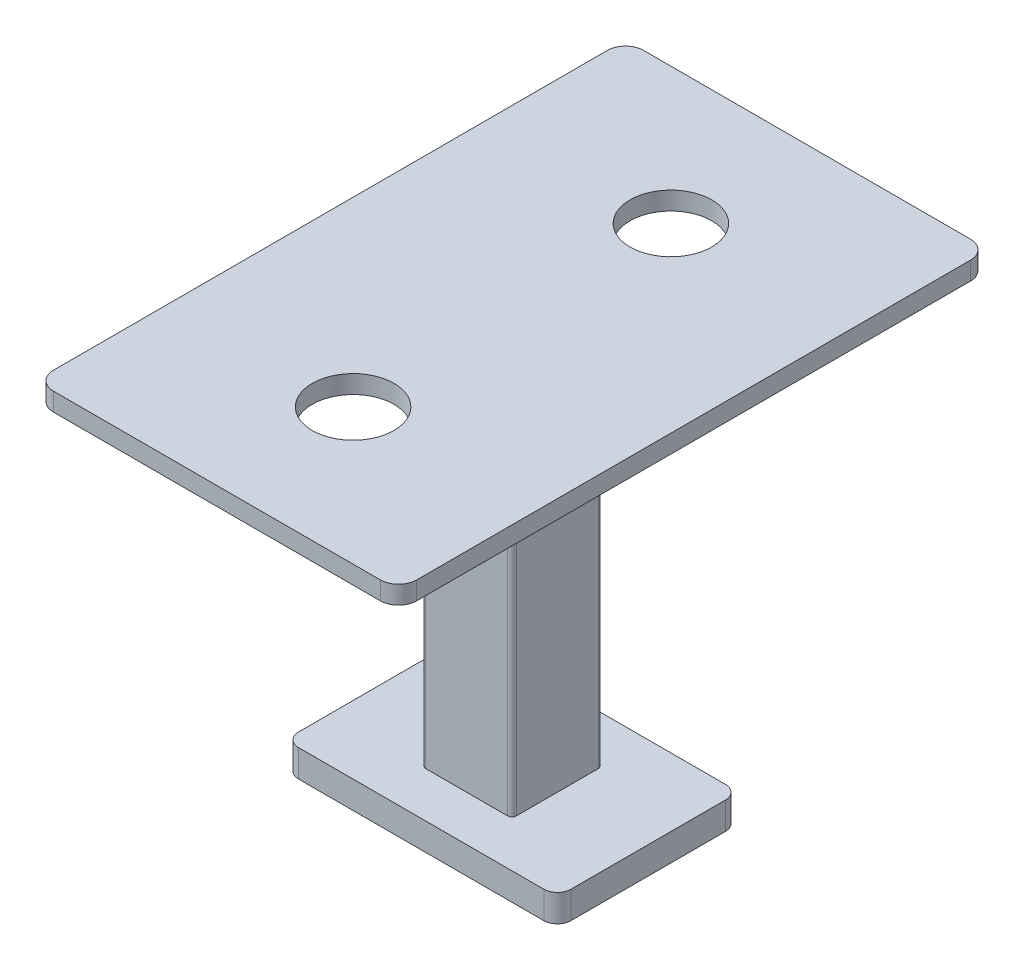
SolidWorks part; units mm, degrees
ref_plane "Front Plane" through (0, 0, 0) normal (0, 0, 1) x (1, 0, 0)
ref_plane "Top Plane" through (0, 0, 0) normal (0, 1, 0) x (1, 0, 0)
ref_plane "Right Plane" through (0, 0, 0) normal (1, 0, 0) x (0, 0, -1)
sketch "Sketch1" plane through (0, 0, 0) normal (0, 1, 0) x (1, 0, 0)
  line L0 (1.5, 0) -> (28.5, 0)
  line L1 (30, 1.5) -> (30, 18.5)
  line L2 (28.5, 20) -> (1.5, 20)
  line L3 (0, 18.5) -> (0, 1.5)
  arc A0 (30, 18.5) -> (28.5, 20) centre (28.5, 18.5) ccw
  arc A1 (30, 1.5) -> (28.5, 0) centre (28.5, 1.5) cw
  arc A2 (1.5, 0) -> (0, 1.5) centre (1.5, 1.5) cw
  arc A3 (1.5, 20) -> (0, 18.5) centre (1.5, 18.5) ccw
  point P7 (30, 20)
  point P10 (30, 0)
  point P13 (0, 0)
  dimension "D3" = 1.5
  dimension "D1" = 30
  dimension "D2" = 20
extrude "Boss-Extrude1" add sketch "Sketch1" along normal blind 3 contours L2 A3 L3 A2 L0 A1 L1 A0
sketch "Sketch3" plane through (0, 3, 0) normal (0, 1, 0) x (1, 0, 0)
  line L0 (15, 20) -> (15, 0) construction
  line L1 (28.5, 20) -> (1.5, 20) construction
  line L2 (1.5, 0) -> (28.5, 0) construction
  line L3 (0, 10) -> (30, 10) construction
  line L4 (0, 18.5) -> (0, 1.5) construction
  line L5 (30, 1.5) -> (30, 18.5) construction
  line L7 (10.5, 5) -> (19.5, 5)
  line L8 (10, 5.5) -> (10, 14.5)
  line L9 (10.5, 15) -> (19.5, 15)
  line L10 (20, 5.5) -> (20, 14.5)
  line L11 (10, 5) -> (20, 15) construction
  line L12 (10, 15) -> (20, 5) construction
  arc A0 (20, 14.5) -> (19.5, 15) centre (19.5, 14.5) ccw
  arc A1 (20, 5.5) -> (19.5, 5) centre (19.5, 5.5) cw
  arc A2 (10.5, 5) -> (10, 5.5) centre (10.5, 5.5) cw
  arc A3 (10.5, 15) -> (10, 14.5) centre (10.5, 14.5) ccw
  point P12 (15, 10)
  dimension "D3" = 0.5
  dimension "D1" = 10
  dimension "D2" = 10
extrude "Boss-Extrude2" add sketch "Sketch3" along normal blind 41
sketch "Sketch4" plane through (0, 44, 0) normal (0, 1, 0) x (1, 0, 0)
  line L0 (10.1464, 14.8536) -> (19.8536, 5.1464) construction
  line L1 (10.1464, 5.1464) -> (19.8536, 14.8536) construction
  line L9 (33, -22.5) -> (-3, -22.5)
  line L10 (35, -20.5) -> (35, 40.5)
  line L11 (33, 42.5) -> (-3, 42.5)
  line L12 (-5, -20.5) -> (-5, 40.5)
  line L13 (35, -22.5) -> (-5, 42.5) construction
  line L14 (35, 42.5) -> (-5, -22.5) construction
  arc A0 (10.5, 15) -> (10, 14.5) centre (10.5, 14.5) ccw construction
  arc A1 (19.5, 5) -> (20, 5.5) centre (19.5, 5.5) ccw construction
  arc A2 (10, 5.5) -> (10.5, 5) centre (10.5, 5.5) ccw construction
  arc A3 (20, 14.5) -> (19.5, 15) centre (19.5, 14.5) ccw construction
  arc A8 (-3, -22.5) -> (-5, -20.5) centre (-3, -20.5) cw
  arc A9 (33, -22.5) -> (35, -20.5) centre (33, -20.5) ccw
  arc A10 (35, 40.5) -> (33, 42.5) centre (33, 40.5) ccw
  arc A11 (-3, 42.5) -> (-5, 40.5) centre (-3, 40.5) ccw
  point P16 (15, 10)
  point P33 (15, 10)
  dimension "D4" = 2
  dimension "D5" = 40
  dimension "D6" = 65
extrude "Boss-Extrude3" add sketch "Sketch4" along normal blind 2
sketch "Sketch5" plane through (0, 46, 0) normal (0, 1, 0) x (1, 0, 0)
  line L0 (33, 42.5) -> (-3, 42.5) construction
  line L1 (-3, -22.5) -> (33, -22.5) construction
  circle A0 centre (15, 27.5) radius 4.5
  circle A1 centre (15, -7.5) radius 4.5
  point P4 (0, 0)
  point P7 (15, 42.5)
  dimension "D1" = 9
  dimension "D2" = 15
  dimension "D3" = 15
extrude "Cut-Extrude1" cut sketch "Sketch5" against normal up to surface (2 mm away) up to face at (15, 44, -10)
